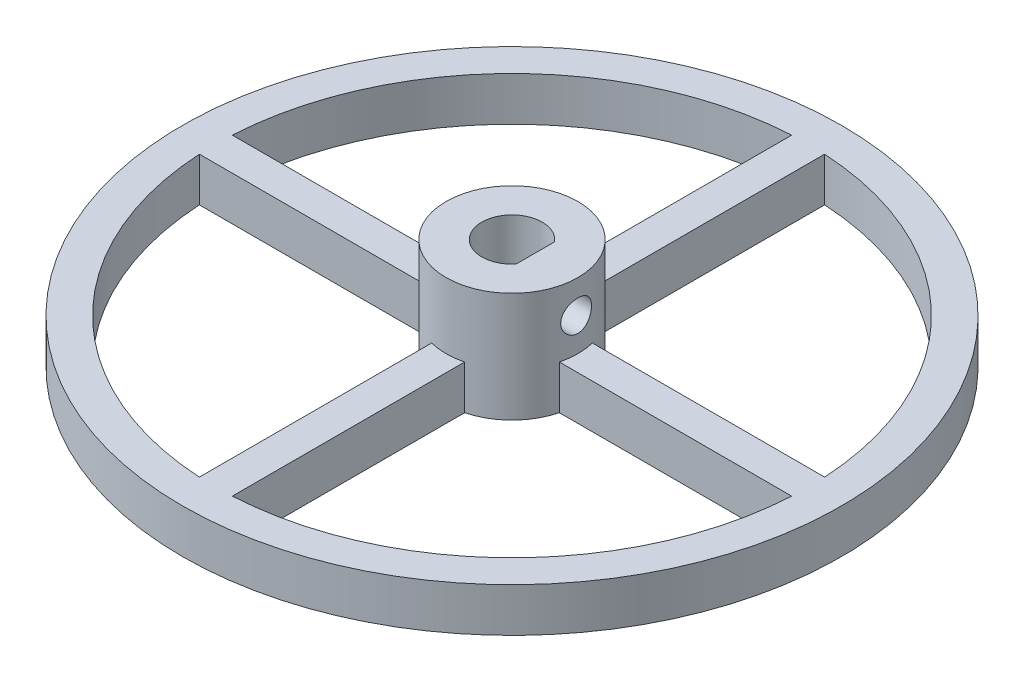
SolidWorks part; units mm, degrees
ref_plane "Front Plane" through (0, 0, 0) normal (0, 0, 1) x (1, 0, 0)
ref_plane "Top Plane" through (0, 0, 0) normal (0, 1, 0) x (1, 0, 0)
ref_plane "Right Plane" through (0, 0, 0) normal (1, 0, 0) x (0, 0, -1)
sketch "Sketch1" plane through (0, 0, 0) normal (0, 1, 0) x (1, 0, 0)
  circle A0 centre (0, 0) radius 30
  dimension "D1" = 60
extrude "Boss-Extrude1" add sketch "Sketch1" along normal blind 4
sketch "Sketch2" plane through (0, 4, 0) normal (0, 1, 0) x (1, 0, 0)
  circle A0 centre (0, 0) radius 6
  dimension "D1" = 12
extrude "Boss-Extrude2" add sketch "Sketch2" along normal blind 6
sketch "Sketch3" plane through (0, 10, 0) normal (0, 1, 0) x (1, 0, 0)
  line L0 (2.1213, 1.75) -> (2.1213, -1.75)
  circle A0 centre (0, 0) radius 2.75
  dimension "D2" = 5.5
  dimension "D1" = 3.5
extrude "Cut-Extrude1" cut sketch "Sketch3" against normal through all contours L0 A0
sketch "Sketch4" plane through (2.1213, 0, 0) normal (-1, 0, 0) x (0, 0, 1)
  line L0 (-1.75, 10) -> (1.75, 10) construction
  circle A0 centre (0, 7) radius 1.4
  dimension "D2" = 2.8
  dimension "D1" = 3
extrude "Cut-Extrude2" cut sketch "Sketch4" against normal blind 5
sketch "Sketch5" plane through (0, 0, 0) normal (0, -1, 0) x (-1, 0, 0)
  line L0 (27, 0) -> (6, 0) construction
  line L1 (6, 0) -> (0, 6) construction
  line L2 (0, 6) -> (0, 27) construction
  line L3 (0, 27) -> (-27, 0) construction
  line L4 (-27, 0) -> (-6, 0) construction
  line L5 (-6, 0) -> (0, -6) construction
  line L6 (0, -6) -> (0, -25.4305) construction
  line L8 (26.9583, -1.5) -> (5.8095, -1.5)
  line L9 (26.9583, -1.5) -> (26.9583, 1.5)
  line L10 (26.9583, 1.5) -> (5.8095, 1.5)
  line L11 (5.8095, -1.5) -> (5.8095, 1.5)
  line L12 (-1.5, 26.9583) -> (1.5, 26.9583)
  line L13 (-1.5, 26.9583) -> (-1.5, 5.8095)
  line L14 (-1.5, 5.8095) -> (1.5, 5.8095)
  line L15 (1.5, 26.9583) -> (1.5, 5.8095)
  line L16 (-26.9583, 1.5) -> (-5.8095, 1.5)
  line L17 (-26.9583, 1.5) -> (-26.9583, -1.5)
  line L18 (-26.9583, -1.5) -> (-5.8095, -1.5)
  line L19 (-5.8095, 1.5) -> (-5.8095, -1.5)
  line L20 (-1.5, -26.9583) -> (1.5, -26.9583)
  line L21 (-1.5, -26.9583) -> (-1.5, -5.8095)
  line L22 (-1.5, -5.8095) -> (1.5, -5.8095)
  line L23 (1.5, -26.9583) -> (1.5, -5.8095)
  circle A0 centre (0, 0) radius 27
  circle A1 centre (0, 0) radius 6
  circle A2 centre (0, 0) radius 30 construction
  dimension "D9" = 12
  dimension "D10" = 3
  dimension "D1" = 1.5
  dimension "D2" = 3
  dimension "D3" = 3
  dimension "D4" = 1.5
  dimension "D5" = 3
  dimension "D6" = 1.5
  dimension "D7" = 3
  dimension "D8" = 1.5
extrude "Cut-Extrude3" cut sketch "Sketch5" against normal through all contours A1 L23 A0 L8 | A1 L18 A0 L21 | A1 L13 A0 L16 | A1 L10 A0 L15
